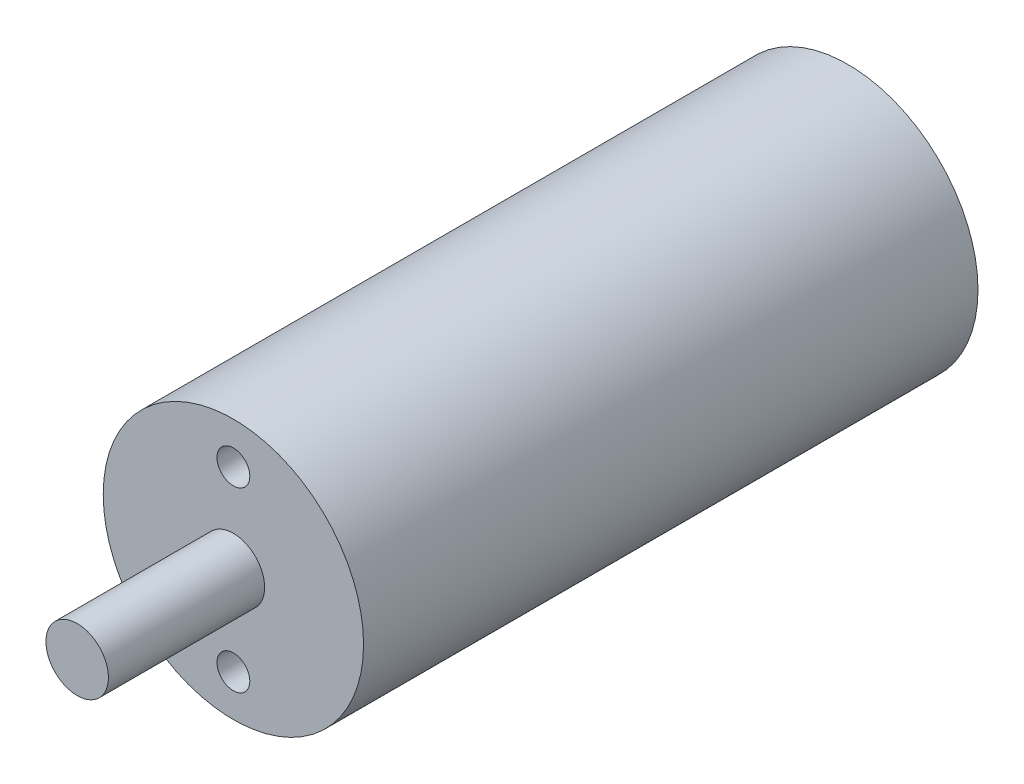
SolidWorks part; units mm, degrees
ref_plane "Front Plane" through (0, 0, 0) normal (0, 0, 1) x (1, 0, 0)
ref_plane "Top Plane" through (0, 0, 0) normal (0, 1, 0) x (1, 0, 0)
ref_plane "Right Plane" through (0, 0, 0) normal (1, 0, 0) x (0, 0, -1)
sketch "Sketch1" plane through (0, 0, 0) normal (0, 0, 1) x (1, 0, 0)
  circle A0 centre (-10.3914, 5.8759) radius 12.5
  dimension "D1" = 25
extrude "Boss-Extrude1" add sketch "Sketch1" along normal blind 59
sketch "Sketch2" plane through (0, 0, 59) normal (0, 0, 1) x (1, 0, 0)
  line L0 (2.1086, 5.8759) -> (-22.8914, 5.8759) construction
  line L1 (-10.3914, -6.6241) -> (-10.3914, 18.3759) construction
  circle A0 centre (-10.3914, 14.3976) radius 1.575
  circle A1 centre (-10.3914, 5.8759) radius 12.5 construction
  circle A2 centre (-10.3914, -2.6458) radius 1.575
  dimension "D3" = 3.15
  dimension "D1" = 0
  dimension "D2" = 8.5217
extrude "Cut-Extrude1" cut sketch "Sketch2" against normal blind 12.7
sketch "Sketch3" plane through (0, 0, 59) normal (0, 0, 1) x (1, 0, 0)
  line L0 (-22.8914, 5.8759) -> (2.1086, 5.8759) construction
  line L1 (-10.3914, -6.6241) -> (-10.3914, 18.3759) construction
  circle A0 centre (-10.3914, 5.8759) radius 3
  circle A1 centre (-10.3914, 5.8759) radius 12.5 construction
  dimension "D3" = 6
  dimension "D1" = 0
  dimension "D2" = 0
extrude "Boss-Extrude2" add sketch "Sketch3" along normal blind 15
